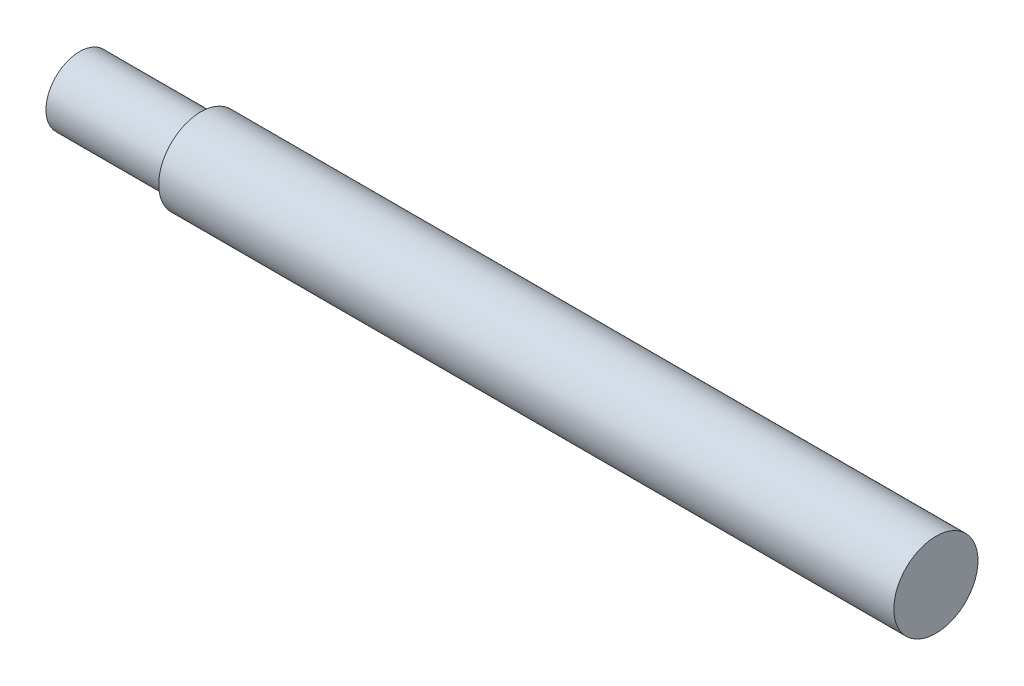
SolidWorks part; units mm, degrees
material "2024-T4"
ref_plane "Front Plane" through (0, 0, 0) normal (0, 0, 1) x (1, 0, 0)
ref_plane "Top Plane" through (0, 0, 0) normal (0, 1, 0) x (1, 0, 0)
ref_plane "Right Plane" through (0, 0, 0) normal (1, 0, 0) x (0, 0, -1)
sketch "Sketch2" plane through (0, 0, 0) normal (1, 0, 0) x (0, 0, -1)
  circle A0 centre (0, 0) radius 3.9688
  dimension "D1" = 7.9375
extrude "Boss-Extrude1" add sketch "Sketch2" along normal blind 69.342
sketch "Sketch3" plane through (0, 0, 0) normal (1, 0, 0) x (0, 0, -1)
  circle A0 centre (0, 0) radius 3.175
  dimension "D1" = 6.35
extrude "Boss-Extrude2" add sketch "Sketch3" against normal blind 11.43
